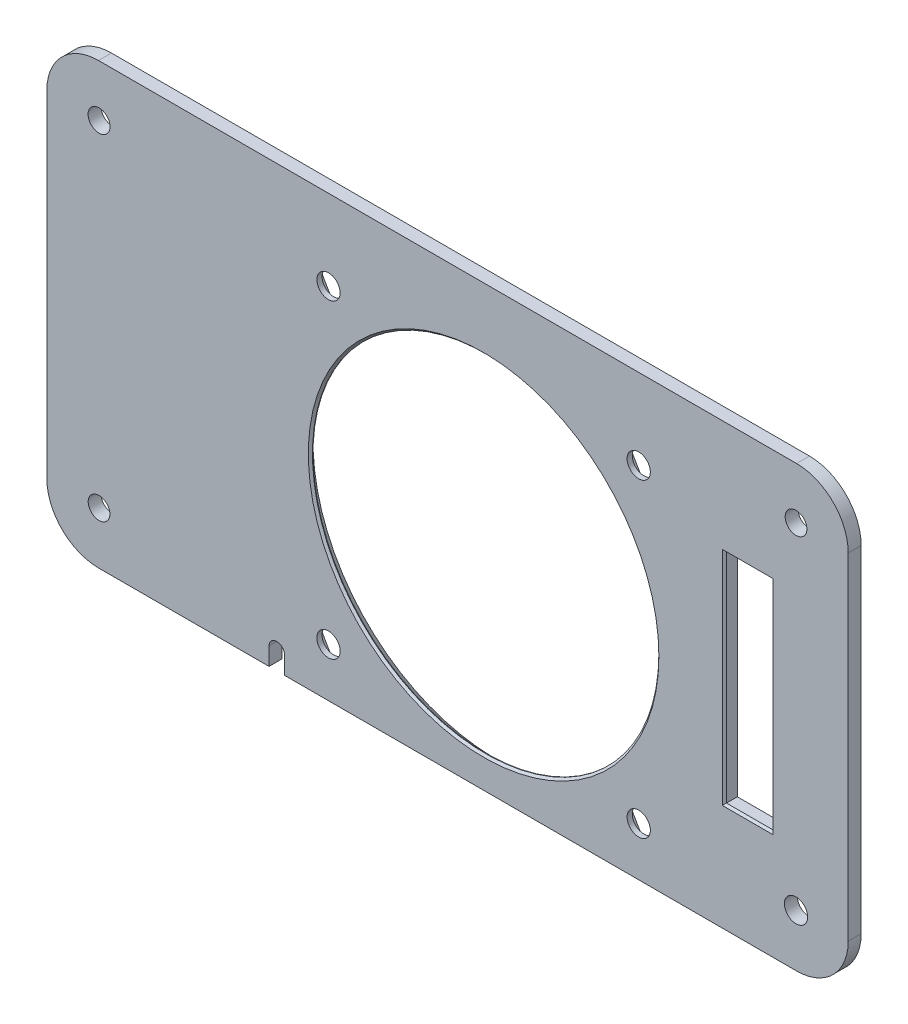
SolidWorks part; units mm, degrees
ref_plane "Front Plane" through (0, 0, 0) normal (0, 0, 1) x (1, 0, 0)
ref_plane "Top Plane" through (0, 0, 0) normal (0, 1, 0) x (1, 0, 0)
ref_plane "Right Plane" through (0, 0, 0) normal (1, 0, 0) x (0, 0, -1)
sketch "Sketch1" plane through (0, 0, 0) normal (0, 0, 1) x (1, 0, 0)
  line L1 (-15.6332, 85.985) -> (119.3668, 85.985)
  line L2 (-25.6332, 75.985) -> (-25.6332, 10.985)
  line L3 (-15.6332, 0.985) -> (119.3668, 0.985)
  line L4 (129.3668, 75.985) -> (129.3668, 10.985)
  line L6 (-16.2457, 0.985) -> (114.3668, 0.985) construction
  arc A0 (-25.6332, 10.985) -> (-15.6332, 0.985) centre (-15.6332, 10.985) ccw
  arc A1 (119.3668, 0.985) -> (129.3668, 10.985) centre (119.3668, 10.985) ccw
  arc A2 (119.3668, 85.985) -> (129.3668, 75.985) centre (119.3668, 75.985) cw
  arc A3 (-15.6332, 85.985) -> (-25.6332, 75.985) centre (-15.6332, 75.985) ccw
  dimension "D1" = 10
  dimension "D2" = 155
  dimension "D3" = 85
extrude "Boss-Extrude1" add sketch "Sketch1" along normal blind 2.5
sketch "Sketch3" plane through (0, 0, 2.5) normal (0, 0, 1) x (1, 0, 0)
  circle A0 centre (119.2668, 11.085) radius 2.25
  circle A1 centre (119.2668, 75.985) radius 2.1
  circle A2 centre (-15.5332, 75.985) radius 2.1213
  circle A3 centre (-15.5332, 11.085) radius 2.1
  dimension "D1" = 4.5
extrude "Cut-Extrude1" cut sketch "Sketch3" against normal blind 3
sketch "Sketch4" plane through (0, 0, 2.5) normal (0, 0, 1) x (1, 0, 0)
  circle A0 centre (58.8425, 40.41) radius 33.5
  circle A1 centre (28.8425, 70.41) radius 2.25
  circle A2 centre (88.8425, 70.41) radius 2.25
  circle A3 centre (88.8425, 10.41) radius 2.25
  circle A4 centre (28.8425, 10.41) radius 2.25
  dimension "D1" = 30
  dimension "D3" = 67
  dimension "D6" = 4.5
  dimension "D2" = 30
  dimension "D5" = 2
  dimension "D4" = 2
extrude "Cut-Extrude2" cut sketch "Sketch4" against normal blind 5
sketch "Sketch5" plane through (0, 0, 0) normal (0, 0, -1) x (-1, 0, 0)
  line L0 (-93.1726, 10.41) -> (-91.0076, 6.66)
  line L1 (-33.1726, 10.41) -> (-31.0076, 6.66)
  line L2 (-31.0076, 6.66) -> (-26.6774, 6.66)
  line L3 (-26.6774, 6.66) -> (-24.5124, 10.41)
  line L4 (-24.5124, 10.41) -> (-26.6774, 14.16)
  line L5 (-26.6774, 14.16) -> (-31.0076, 14.16)
  line L6 (-31.0076, 14.16) -> (-33.1726, 10.41)
  line L7 (-91.0076, 6.66) -> (-86.6774, 6.66)
  line L8 (-86.6774, 6.66) -> (-84.5124, 10.41)
  line L9 (-84.5124, 10.41) -> (-86.6774, 14.16)
  line L10 (-86.6774, 14.16) -> (-91.0076, 14.16)
  line L11 (-91.0076, 14.16) -> (-93.1726, 10.41)
  line L12 (-93.1726, 70.41) -> (-91.0076, 66.66)
  line L13 (-91.0076, 66.66) -> (-86.6774, 66.66)
  line L14 (-86.6774, 66.66) -> (-84.5124, 70.41)
  line L15 (-84.5124, 70.41) -> (-86.6774, 74.16)
  line L16 (-86.6774, 74.16) -> (-91.0076, 74.16)
  line L17 (-91.0076, 74.16) -> (-93.1726, 70.41)
  line L18 (-33.1726, 70.41) -> (-31.0076, 66.66)
  line L19 (-31.0076, 66.66) -> (-26.6774, 66.66)
  line L20 (-26.6774, 66.66) -> (-24.5124, 70.41)
  line L21 (-24.5124, 70.41) -> (-26.6774, 74.16)
  line L22 (-26.6774, 74.16) -> (-31.0076, 74.16)
  line L23 (-31.0076, 74.16) -> (-33.1726, 70.41)
  circle A0 centre (-28.8425, 10.41) radius 3.75 construction
  circle A1 centre (-88.8425, 10.41) radius 3.75 construction
  circle A2 centre (-88.8425, 70.41) radius 3.75 construction
  circle A3 centre (-28.8425, 70.41) radius 3.75 construction
  dimension "D1" = 7.5
  dimension "D2" = 2
extrude "Cut-Extrude3" cut sketch "Sketch5" against normal blind 1.5
chamfer "Chamfer1" distance 2 angle 45 1 edges at (92.3425, 40.41, 0)
sketch "Sketch6" plane through (0, 0, 2.5) normal (0, 0, 1) x (1, 0, 0)
  line L0 (18.8425, 4.41) -> (18.8425, 0.985) construction
  line L1 (20.3425, 4.41) -> (20.3425, 0.985)
  line L2 (17.3425, 4.41) -> (17.3425, 0.985)
  line L3 (-15.6332, 0.985) -> (119.3668, 0.985) construction
  circle A1 centre (28.8425, 10.41) radius 2.25 construction
  arc A3 (20.3425, 4.41) -> (17.3425, 4.41) centre (18.8425, 4.41) ccw
  arc A4 (17.3425, 0.985) -> (20.3425, 0.985) centre (18.8425, 0.985) ccw
  point P7 (18.8425, 2.6975)
  dimension "D1" = 6
  dimension "D2" = 10
extrude "Cut-Extrude4" cut sketch "Sketch6" against normal blind 3
sketch "Sketch7" plane through (0, 0, 0) normal (0, 0, -1) x (-1, 0, 0)
  line L0 (25.6332, 43.485) -> (-121.8668, 43.485) construction
  line L1 (25.6332, 75.985) -> (25.6332, 10.985) construction
  line L4 (20.139, 23.165) -> (-0.181, 23.165) construction
  line L5 (20.139, 23.165) -> (20.139, 63.805) construction
  line L6 (20.139, 63.805) -> (-0.181, 63.805) construction
  line L7 (-0.181, 23.165) -> (-0.181, 63.805) construction
  line L8 (20.139, 23.165) -> (-0.181, 63.805) construction
  line L9 (20.139, 63.805) -> (-0.181, 23.165) construction
  circle A0 centre (18.234, 25.07) radius 1.25
  circle A1 centre (1.724, 25.07) radius 1.25
  circle A2 centre (18.234, 25.07) radius 2.25
  circle A3 centre (1.724, 25.07) radius 2.25
  point P6 (9.979, 43.485)
  dimension "D3" = 16.51
  dimension "D7" = 4.5
  dimension "D6" = 2.5
  dimension "D1" = 40.64
  dimension "D2" = 20.32
  dimension "D4" = 1.905
  dimension "D5" = 1.905
extrude "Boss-Extrude2" add sketch "Sketch7" along normal blind 3
chamfer "Chamfer2" distance 2 angle 45 2 edges at (0.526, 25.07, 0) (-15.984, 25.07, 0)
sketch "Sketch12" plane through (0, 0, 2.5) normal (0, 0, 1) x (1, 0, 0)
  line L1 (105.4127, 64.0346) -> (114.4127, 64.0346)
  line L2 (105.4127, 64.0346) -> (105.4127, 21.9346)
  line L3 (105.4127, 21.9346) -> (114.4127, 21.9346)
  line L4 (114.4127, 64.0346) -> (114.4127, 21.9346)
extrude "Cut-Extrude5" cut sketch "Sketch12" against normal blind 7
chamfer "Chamfer3" distance 0.4 angle 45 5 edges at (92.3425, 40.41, 2.5) (109.9127, 21.9346, 2.5) (114.4127, 42.9846, 2.5) (109.9127, 64.0346, 2.5) (105.4127, 42.9846, 2.5)
